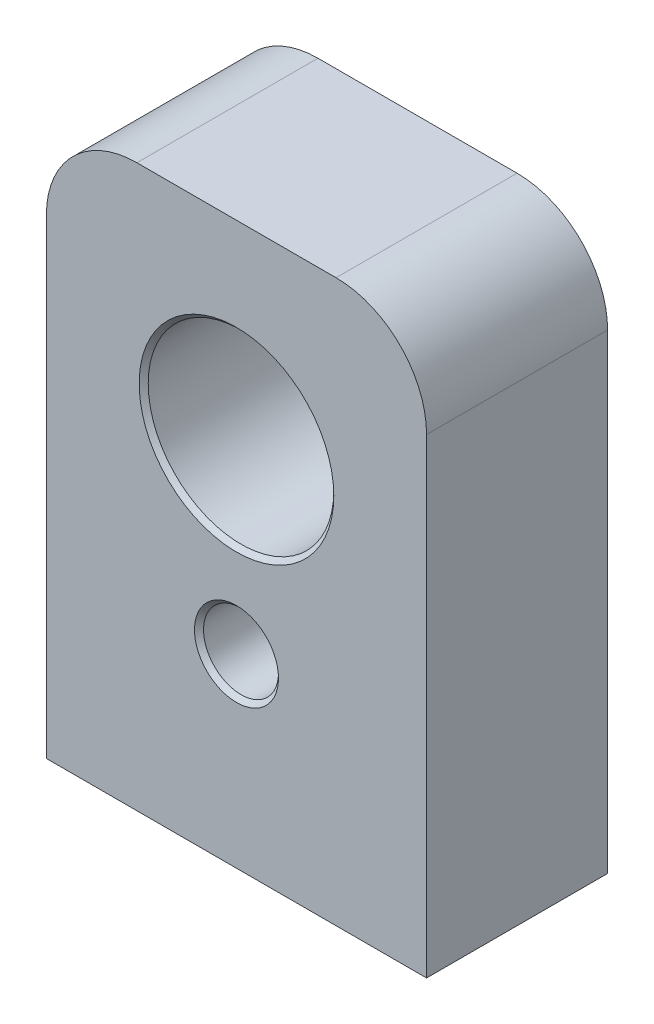
SolidWorks part; units mm, degrees
ref_plane "Front Plane" through (0, 0, 0) normal (0, 0, 1) x (1, 0, 0)
ref_plane "Top Plane" through (0, 0, 0) normal (0, 1, 0) x (1, 0, 0)
ref_plane "Right Plane" through (0, 0, 0) normal (1, 0, 0) x (0, 0, -1)
sketch "Sketch1" plane through (0, 0, 0) normal (0, 0, 1) x (1, 0, 0)
  line L0 (2.5551, -31.5193) -> (-39.4449, -31.5193) construction
  line L2 (-39.4449, 30.4807) -> (-39.4449, -7.5193) construction
  line L4 (2.5551, 30.4807) -> (-39.4449, 30.4807) construction
  line L5 (2.5551, -22.5193) -> (2.5551, 30.4807) construction
  line L8 (-7.4449, 30.4807) -> (-29.4449, 30.4807)
  line L9 (-39.4449, 20.4807) -> (-39.4449, -31.5193)
  line L10 (-39.4449, -31.5193) -> (2.5551, -31.5193)
  line L11 (2.5551, -31.5193) -> (2.5551, 20.4807)
  circle A0 centre (-18.4449, 9.4807) radius 10.25
  circle A1 centre (-18.4449, -11.0193) radius 4.14
  arc A2 (2.5551, 20.4807) -> (-7.4449, 30.4807) centre (-7.4449, 20.4807) ccw
  arc A3 (-39.4449, 20.4807) -> (-29.4449, 30.4807) centre (-29.4449, 20.4807) cw
  dimension "D2" = 10
  dimension "D1" = 8.28
  dimension "D3" = 20.5
extrude "Boss-Extrude1" add sketch "Sketch1" against normal mid plane 20
chamfer "Chamfer1" distance 0.5 angle 45 4 edges at (-8.1949, 9.4807, 10) (-8.1949, 9.4807, -10) (-14.3049, -11.0193, -10) (-14.3049, -11.0193, 10)
sketch "Sketch3" plane through (0, -31.5193, 0) normal (0, -1, 0) x (-1, 0, 0)
  line L0 (39.4449, 0) -> (-2.5551, 0) construction
  line L1 (33.4449, -3.25) -> (36.2595, -1.625)
  line L2 (36.2595, -1.625) -> (36.2595, 1.625)
  line L3 (36.2595, 1.625) -> (33.4449, 3.25)
  line L4 (33.4449, 3.25) -> (30.6303, 1.625)
  line L5 (30.6303, 1.625) -> (30.6303, -1.625)
  line L6 (30.6303, -1.625) -> (33.4449, -3.25)
  line L7 (39.4449, 10) -> (39.4449, -10) construction
  line L8 (-2.5551, 10) -> (-2.5551, -10) construction
  circle A0 centre (33.4449, 0) radius 2.8146 construction
  point P14 (0, 0)
  point P15 (0, 0)
  point P16 (33.4449, -3)
  dimension "D1" = 6
  dimension "D2" = 6.5
extrude "Cut-Extrude1" cut sketch "Sketch3" against normal blind 15.5
ref_plane "Plane1" through (-18.4449, 0, 0) normal (1, 0, 0) x (0, 0, -1)
mirror "Mirror1" about plane through (-18.4449, 0, 0) normal (1, 0, 0) of "Cut-Extrude1"
